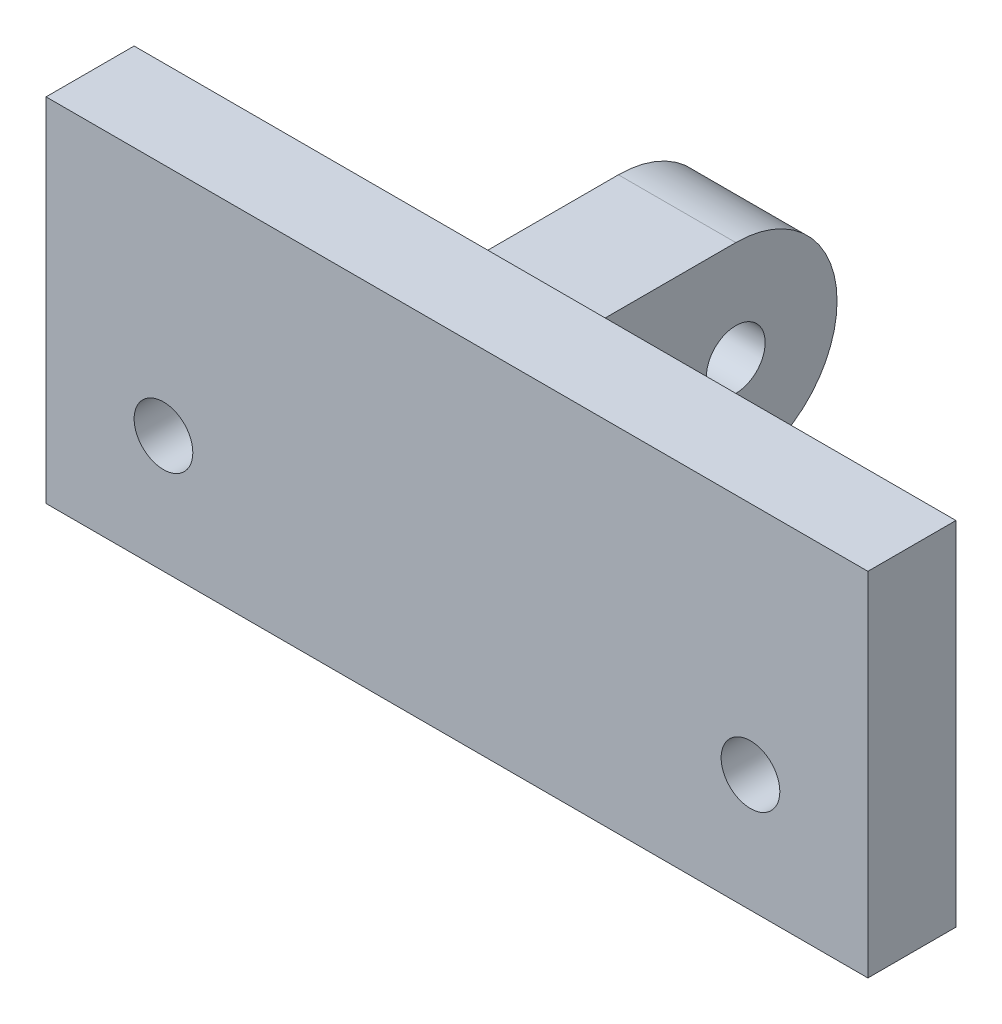
SolidWorks part; units mm, degrees
ref_plane "Alzado" through (0, 0, 0) normal (0, 0, 1) x (1, 0, 0)
ref_plane "Planta" through (0, 0, 0) normal (0, 1, 0) x (1, 0, 0)
ref_plane "Vista lateral" through (0, 0, 0) normal (1, 0, 0) x (0, 0, -1)
sketch "Croquis1" plane through (0, 0, 0) normal (0, 0, 1) x (1, 0, 0)
  line L1 (-30.4122, 13.3566) -> (-2.4122, 13.3566)
  line L2 (-30.4122, 13.3566) -> (-30.4122, 1.3566)
  line L3 (-30.4122, 1.3566) -> (-2.4122, 1.3566)
  line L4 (-2.4122, 13.3566) -> (-2.4122, 1.3566)
  dimension "D1" = 28
  dimension "D2" = 12
extrude "Saliente-Extruir1" add sketch "Croquis1" along normal blind 3
sketch "Croquis2" plane through (0, 0, 3) normal (0, 0, 1) x (1, 0, 0)
  line L1 (-2.4122, 1.3566) -> (-2.4122, 13.3566) construction
  line L2 (-30.4122, 1.3566) -> (-2.4122, 1.3566) construction
  circle A0 centre (-26.4122, 5.3566) radius 1
  circle A1 centre (-6.4122, 5.3566) radius 1
  dimension "D1" = 20
  dimension "D2" = 4
  dimension "D3" = 4
extrude "Cortar-Extruir1" cut sketch "Croquis2" against normal up to vertex (3 mm away)
sketch "Croquis3" plane through (0, 0, 0) normal (0, 0, -1) x (-1, 0, 0)
  line L0 (2.4122, 13.3566) -> (30.4122, 13.3566) construction
  line L1 (17.9122, 13.3566) -> (14.9122, 13.3566)
  line L2 (17.9122, 13.3566) -> (17.9122, 4.9645)
  line L3 (17.9122, 4.9645) -> (14.9122, 4.9645)
  line L4 (14.9122, 13.3566) -> (14.9122, 4.9645)
  line L5 (30.4122, 13.3566) -> (30.4122, 1.3566) construction
  dimension "D1" = 3
  dimension "D2" = 12.5
extrude "Saliente-Extruir2" add sketch "Croquis3" along normal blind 8
sketch "Croquis4" plane through (-17.9122, 0, 0) normal (-1, 0, 0) x (0, 0, 1)
  line L0 (-8, 4.9645) -> (-8, 13.3566) construction
  line L1 (-8, 13.3566) -> (0, 13.3566) construction
  circle A0 centre (-4.5, 9.8566) radius 1
  dimension "D1" = 3.5
  dimension "D2" = 3.5
extrude "Cortar-Extruir2" cut sketch "Croquis4" against normal up to vertex (3 mm away)
sketch "Croquis6" plane through (-17.9122, 0, 0) normal (-1, 0, 0) x (0, 0, 1)
  line L0 (-8, 13.3566) -> (-4.5, 13.3566)
  line L1 (-8, 13.3566) -> (-8, 6.3521)
  line L2 (-8, 4.9645) -> (-8, 13.3566) construction
  line L3 (-4.5, 6.4066) -> (0, 6.4066)
  line L4 (0, 4.9645) -> (0, 13.3566) construction
  line L5 (0, 6.4066) -> (0, 4.9645)
  line L6 (0, 4.9645) -> (-8, 4.9645)
  line L7 (-8, 4.9645) -> (-8, 6.3521)
  line L8 (-8, 13.3566) -> (0, 13.3566) construction
  line L9 (-4.5, 13.3566) -> (0, 13.3566)
  line L10 (0, 13.3566) -> (0, 13.3066)
  line L11 (0, 13.3066) -> (-4.5, 13.3066)
  arc A0 (-4.5, 6.4066) -> (-4.5, 13.3066) centre (-4.5, 9.8566) cw
extrude "Cortar-Extruir3" cut sketch "Croquis6" against normal blind 8
sketch "Croquis8" plane through (0, 0, 0) normal (0, 0, -1) x (-1, 0, 0)
  circle A0 centre (26.4122, 5.3566) radius 1
  circle A1 centre (6.4122, 5.3566) radius 1
  circle A2 centre (6.4122, 5.3566) radius 2
  circle A3 centre (26.4122, 5.3566) radius 2
sketch "Croquis11" plane through (-17.9122, 0, 0) normal (-1, 0, 0) x (0, 0, 1)
  line L0 (-4.5, 6.4066) -> (0, 6.4066)
  line L1 (0, 6.4066) -> (0, 13.3066)
  line L2 (0, 13.3066) -> (-4.5, 13.3066)
  arc A0 (-4.5, 6.4066) -> (-4.5, 13.3066) centre (-4.5, 9.8566) cw
  circle A1 centre (-4.5, 9.8566) radius 1
extrude "Saliente-Extruir4" add sketch "Croquis11" along normal blind 0.5
sketch "Croquis12" plane through (-14.9122, 0, 0) normal (1, 0, 0) x (0, 0, -1)
  line L0 (4.5, 13.3066) -> (0, 13.3066)
  line L1 (0, 13.3066) -> (0, 6.4066)
  line L2 (0, 6.4066) -> (4.5, 6.4066)
  arc A0 (4.5, 13.3066) -> (4.5, 6.4066) centre (4.5, 9.8566) cw
  circle A1 centre (4.5, 9.8566) radius 1
extrude "Saliente-Extruir5" add sketch "Croquis12" along normal blind 0.5
